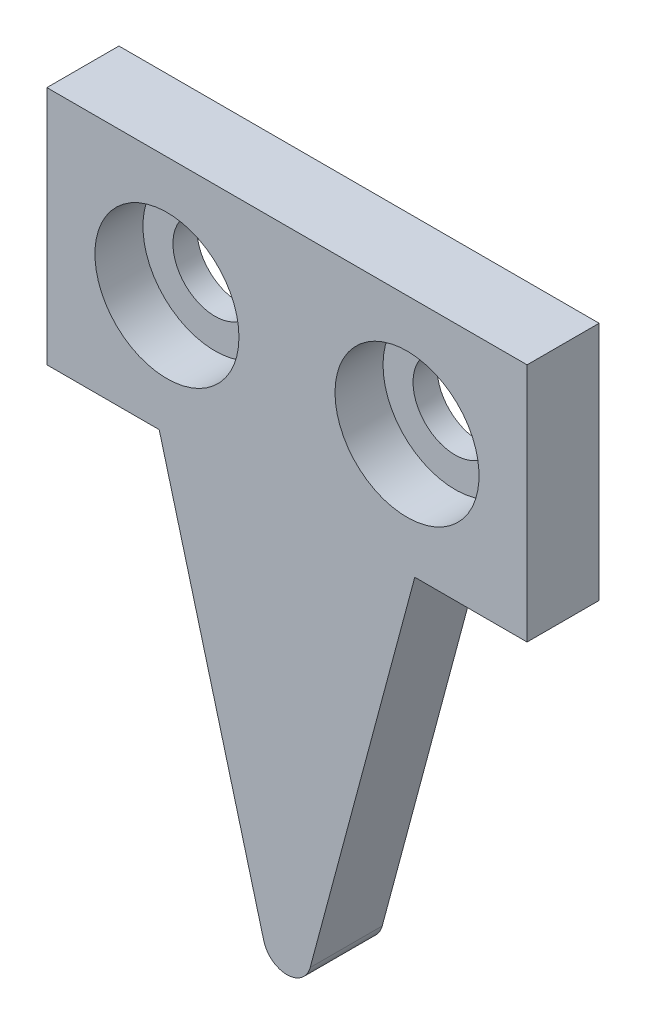
SolidWorks part; units mm, degrees
ref_plane "Front Plane" through (0, 0, 0) normal (0, 0, 1) x (1, 0, 0)
ref_plane "Top Plane" through (0, 0, 0) normal (0, 1, 0) x (1, 0, 0)
ref_plane "Right Plane" through (0, 0, 0) normal (1, 0, 0) x (0, 0, -1)
sketch "Sketch2" plane through (0, 0, 0) normal (0, 0, 1) x (1, 0, 0)
  line L1 (-5.3225, 16) -> (-0.9659, -0.2588)
  line L3 (0, -11.1651) -> (0, 29.6028) construction
  line L6 (-5.3225, 16) -> (-10, 16)
  line L7 (-10, 16) -> (-10, 26)
  line L8 (-10, 26) -> (10, 26)
  line L9 (10, 16) -> (10, 26)
  line L10 (5.3225, 16) -> (10, 16)
  line L11 (5.3225, 16) -> (0.9659, -0.2588)
  arc A0 (-0.9659, -0.2588) -> (0.9659, -0.2588) centre (0, 0) ccw
  point P5 (0, 26)
  point P11 (0, 26)
  point P13 (0, -1)
  dimension "D4" = 1
  dimension "D1" = 10
  dimension "D2" = 17
  dimension "D3" = 20
  dimension "D5" = 105
extrude "Boss-Extrude1" add sketch "Sketch2" along normal blind 3
sketch "Sketch3" plane through (0, 0, 3) normal (0, 0, 1) x (1, 0, 0)
  line L3 (-10, 26) -> (-10, 16) construction
  line L4 (0, -1) -> (0, 26) construction
  line L5 (10, 26) -> (-10, 26) construction
  circle A0 centre (-5, 21) radius 1.75
  arc A1 (-0.9659, -0.2588) -> (0.9659, -0.2588) centre (0, 0) ccw construction
  circle A2 centre (5, 21) radius 1.75
  point P9 (-10, 21)
  dimension "D1" = 3.5
  dimension "D2" = 5
  dimension "D3" = 5
extrude "Cut-Extrude1" cut sketch "Sketch3" against normal up to surface (3 mm away) up to face at (0, 14.3426, 0)
sketch "Sketch5" plane through (0, 0, 3) normal (0, 0, 1) x (1, 0, 0)
  line L0 (0, -1) -> (0, 26) construction
  line L1 (10, 26) -> (-10, 26) construction
  line L2 (-10, 26) -> (-10, 16) construction
  arc A0 (-0.9659, -0.2588) -> (0.9659, -0.2588) centre (0, 0) ccw construction
  circle A1 centre (-5, 21) radius 3
  circle A2 centre (5, 21) radius 3
  point P12 (-10, 21)
  dimension "D1" = 6
  dimension "D2" = 5
extrude "Cut-Extrude2" cut sketch "Sketch5" against normal blind 2
